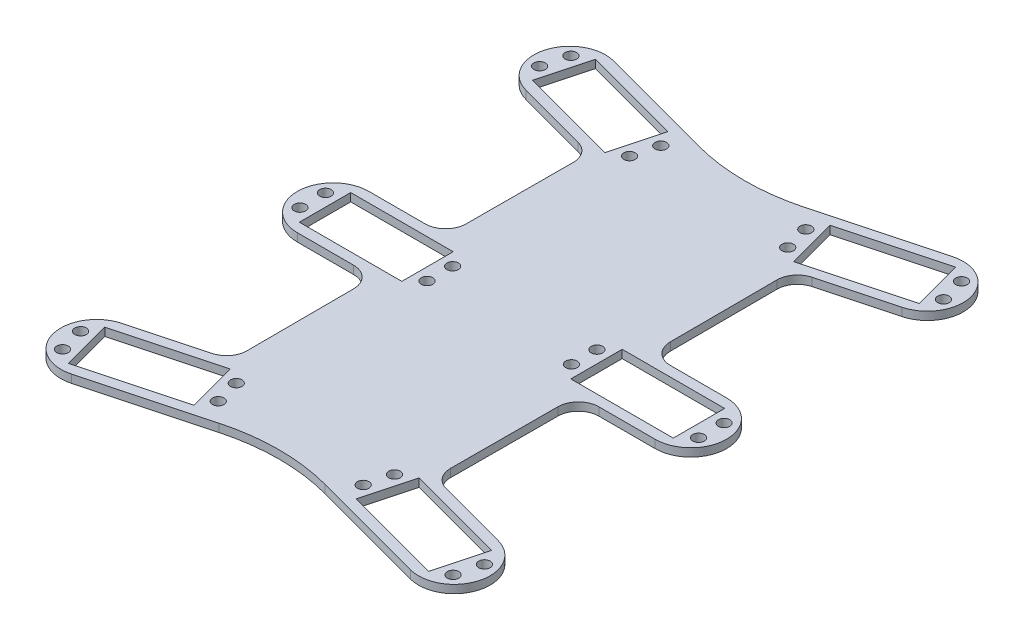
SolidWorks part; units mm, degrees
ref_plane "Front Plane" through (0, 0, 0) normal (0, 0, 1) x (1, 0, 0)
ref_plane "Top Plane" through (0, 0, 0) normal (0, 1, 0) x (1, 0, 0)
ref_plane "Right Plane" through (0, 0, 0) normal (1, 0, 0) x (0, 0, -1)
sketch "Sketch1" plane through (0, 0, 0) normal (0, 1, 0) x (1, 0, 0)
  line L0 (0, 32.1883) -> (0, -21.4181) construction
  line L1 (0, 0) -> (27.1703, 0) construction
  line L2 (-70, 14) -> (-40, 14)
  line L3 (-40, 14) -> (-39.8161, 70)
  line L4 (-39.8161, 70) -> (-73.6235, 79.0587)
  line L5 (-66.3765, 106.1046) -> (0, 88.3191)
  line L10 (-66.3765, 106.1046) -> (-73.6235, 79.0587) construction
  line L12 (-70, 14) -> (-70, -14) construction
  line L14 (-66.3765, -106.1046) -> (0, -88.3191)
  line L15 (-39.8161, -70) -> (-73.6235, -79.0587)
  line L16 (-40, -14) -> (-39.8161, -70)
  line L17 (-70, -14) -> (-40, -14)
  line L18 (66.3765, -106.1046) -> (0, -88.3191)
  line L19 (66.3765, 106.1046) -> (0, 88.3191)
  line L20 (70, 14) -> (70, -14) construction
  line L21 (66.3765, 106.1046) -> (73.6235, 79.0587) construction
  line L22 (70, -14) -> (40, -14)
  line L23 (40, -14) -> (39.8161, -70)
  line L24 (39.8161, -70) -> (73.6235, -79.0587)
  line L25 (39.8161, 70) -> (73.6235, 79.0587)
  line L26 (40, 14) -> (39.8161, 70)
  line L27 (70, 14) -> (40, 14)
  line L28 (-70.4609, 103.1096) -> (-75.6631, 83.6945)
  line L29 (-75.6631, 83.6945) -> (-36.9295, 73.3159)
  line L30 (-36.9295, 73.3159) -> (-31.7272, 92.731)
  line L31 (-31.7272, 92.731) -> (-70.4609, 103.1096)
  line L32 (-51.094, 97.9203) -> (-56.2963, 78.5052) construction
  line L33 (-70, 92.5816) -> (-73.062, 93.4021) construction
  line L34 (-53.12, 10.05) -> (-53.12, -10.05) construction
  line L35 (-73.17, 10.05) -> (-33.07, 10.05)
  line L36 (-73.17, 10.05) -> (-73.17, -10.05)
  line L37 (-73.17, -10.05) -> (-33.07, -10.05)
  line L38 (-33.07, 10.05) -> (-33.07, -10.05)
  line L39 (-73.17, 10.05) -> (-33.07, -10.05) construction
  line L40 (-73.17, -10.05) -> (-33.07, 10.05) construction
  line L41 (-36.9295, -73.3159) -> (-31.7272, -92.731)
  line L42 (-31.7272, -92.731) -> (-70.4609, -103.1096)
  line L43 (-70.4609, -103.1096) -> (-75.6631, -83.6945)
  line L44 (-75.6631, -83.6945) -> (-36.9295, -73.3159)
  line L45 (36.9295, 73.3159) -> (31.7272, 92.731)
  line L46 (75.6631, 83.6945) -> (36.9295, 73.3159)
  line L47 (70.4609, 103.1096) -> (75.6631, 83.6945)
  line L48 (31.7272, 92.731) -> (70.4609, 103.1096)
  line L49 (73.17, -10.05) -> (33.07, 10.05) construction
  line L50 (73.17, 10.05) -> (33.07, -10.05) construction
  line L51 (53.12, 10.05) -> (53.12, -10.05) construction
  line L52 (33.07, 10.05) -> (33.07, -10.05)
  line L53 (73.17, -10.05) -> (33.07, -10.05)
  line L54 (73.17, 10.05) -> (73.17, -10.05)
  line L55 (73.17, 10.05) -> (33.07, 10.05)
  line L56 (36.9295, -73.3159) -> (31.7272, -92.731)
  line L57 (75.6631, -83.6945) -> (36.9295, -73.3159)
  line L58 (31.7272, -92.731) -> (70.4609, -103.1096)
  line L59 (70.4609, -103.1096) -> (75.6631, -83.6945)
  line L60 (-76.4333, 99.4818) -> (-79.0215, 89.8226) construction
  line L61 (-77.7274, 94.6522) -> (-70, 92.5816) construction
  line L62 (-78, 5) -> (-78, -5) construction
  arc A0 (-70, 14) -> (-70, -14) centre (-70, 0) ccw
  arc A1 (-66.3765, 106.1046) -> (-73.6235, 79.0587) centre (-70, 92.5816) ccw
  circle A8 centre (-76.4333, 99.4818) radius 2.25
  circle A9 centre (-79.0215, 89.8226) radius 2.25
  circle A10 centre (-78, 5) radius 2.25
  arc A11 (-66.3765, -106.1046) -> (-73.6235, -79.0587) centre (-70, -92.5816) cw
  circle A12 centre (-79.0215, -89.8226) radius 2.25
  circle A13 centre (-76.4333, -99.4818) radius 2.25
  circle A14 centre (-78, -5) radius 2.25
  circle A15 centre (78, -5) radius 2.25
  circle A16 centre (76.4333, -99.4818) radius 2.25
  circle A17 centre (79.0215, -89.8226) radius 2.25
  arc A18 (66.3765, -106.1046) -> (73.6235, -79.0587) centre (70, -92.5816) ccw
  circle A19 centre (78, 5) radius 2.25
  circle A20 centre (79.0215, 89.8226) radius 2.25
  circle A21 centre (76.4333, 99.4818) radius 2.25
  arc A22 (66.3765, 106.1046) -> (73.6235, 79.0587) centre (70, 92.5816) cw
  arc A23 (70, 14) -> (70, -14) centre (70, 0) cw
  circle A24 centre (-30.957, 76.9437) radius 2.25
  circle A25 centre (-28.3688, 86.603) radius 2.25
  circle A26 centre (-28.24, -5) radius 2.25
  circle A27 centre (-28.24, 5) radius 2.25
  circle A28 centre (-28.3688, -86.603) radius 2.25
  circle A29 centre (-30.957, -76.9437) radius 2.25
  circle A30 centre (28.3688, 86.603) radius 2.25
  circle A31 centre (30.957, 76.9437) radius 2.25
  circle A32 centre (28.24, 5) radius 2.25
  circle A33 centre (28.24, -5) radius 2.25
  circle A34 centre (30.957, -76.9437) radius 2.25
  circle A35 centre (28.3688, -86.603) radius 2.25
  point P60 (-51.094, 97.9203)
  point P62 (-56.2963, 78.5052)
  point P65 (-73.062, 93.4021)
  point P71 (-53.12, 0)
  point P108 (53.12, 0)
  point P118 (-83.523, 96.2051)
  dimension "D2" = 14
  dimension "D3" = 10
  dimension "D8" = 4.5
  dimension "D1" = 75
  dimension "D4" = 70
  dimension "D5" = 30
  dimension "D6" = 35
  dimension "D7" = 56
  dimension "D9" = 8
  dimension "D10" = 5
  dimension "D11" = 10
  dimension "D12" = 40.1
  dimension "D13" = 20.1
  dimension "D14" = 4.83
  dimension "D15" = 40.1
  dimension "D16" = 20.1
  dimension "D17" = 4.83
  dimension "D18" = 8
extrude "Boss-Extrude1" add sketch "Sketch1" along normal blind 3.175
fillet "Fillet1" radius 80 2 edges at (0, 1.5875, -88.3191) (0, 1.5875, 88.3191)
fillet "Fillet2" radius 8 8 edges at (39.8161, 1.5875, 70) (40, 1.5875, 14) (40, 1.5875, -14) (39.8161, 1.5875, -70) (-39.8161, 1.5875, -70) (-40, 1.5875, -14) (-40, 1.5875, 14) (-39.8161, 1.5875, 70)
